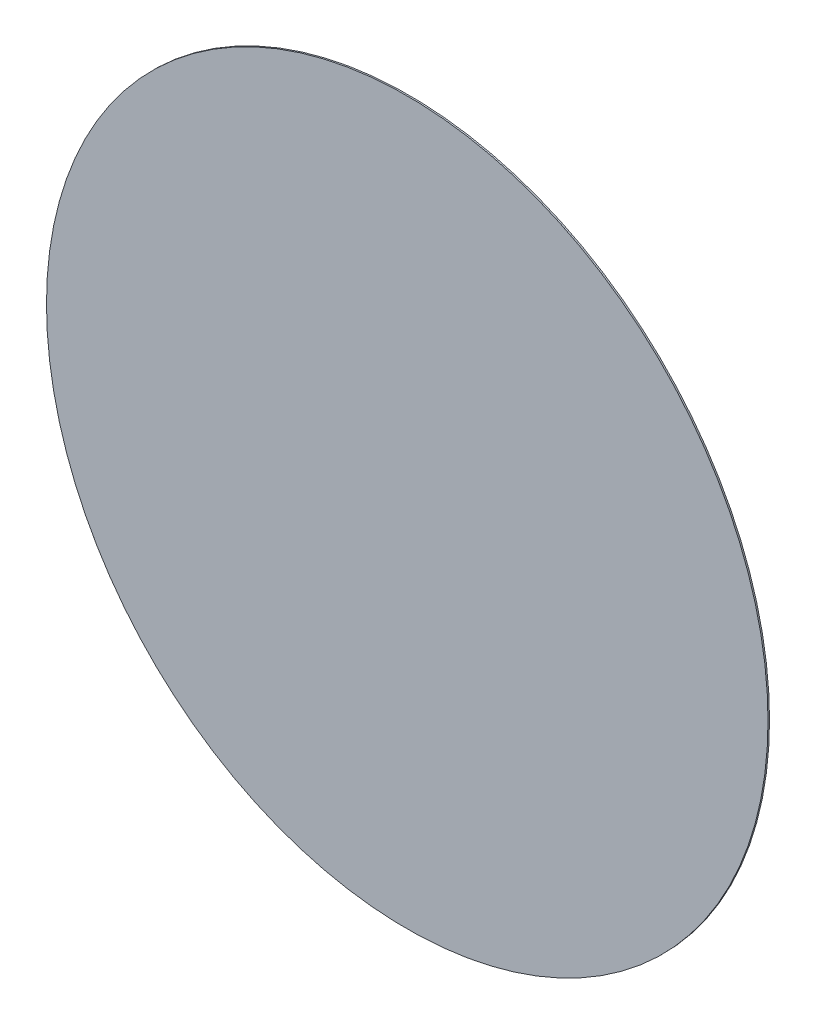
SolidWorks part; units mm, degrees
ref_plane "Front Plane" through (0, 0, 0) normal (0, 0, 1) x (1, 0, 0)
ref_plane "Top Plane" through (0, 0, 0) normal (0, 1, 0) x (1, 0, 0)
ref_plane "Right Plane" through (0, 0, 0) normal (1, 0, 0) x (0, 0, -1)
sketch "Sketch2" plane through (0, 0, 0) normal (0, 0, 1) x (1, 0, 0)
  circle A0 centre (0, 0) radius 47.75
  dimension "D1" = 95.5
extrude "Boss-Extrude1" add sketch "Sketch2" along normal blind 0.2
